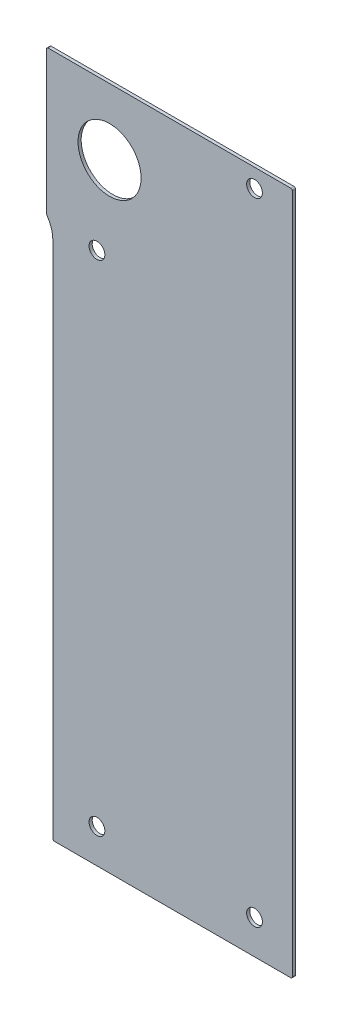
SolidWorks part; units mm, degrees
ref_plane "Ebene vorne" through (0, 0, 0) normal (0, 0, 1) x (1, 0, 0)
ref_plane "Ebene oben" through (0, 0, 0) normal (0, 1, 0) x (1, 0, 0)
ref_plane "Ebene rechts" through (0, 0, 0) normal (1, 0, 0) x (0, 0, -1)
sketch "Sketch1" plane through (0, 0, 0) normal (0, 0, 1) x (1, 0, 0)
  line L0 (2, 0) -> (2, 175) construction
  line L1 (0, 0) -> (76, 0)
  line L2 (0, 0) -> (0, 175)
  line L3 (-19.55, 217) -> (-32, 217)
  line L4 (76, 0) -> (76, 217)
  line L5 (0, 175) -> (-32, 175)
  line L6 (-19.55, 217) -> (-19.55, 212)
  line L7 (76, 217) -> (-12.55, 217)
  line L8 (-32, 175) -> (-32, 217)
  line L9 (-19.55, 212) -> (-12.55, 212)
  line L10 (-12.55, 217) -> (-12.55, 212)
  line L11 (-19.55, 205.875) -> (-12.55, 205.875) construction
  line L12 (-19.55, 207) -> (-12.55, 207)
  line L13 (-19.55, 204.75) -> (-12.55, 204.75)
  circle A0 centre (14, 169.15) radius 2.5
  circle A1 centre (14, 10.85) radius 2.5
  circle A2 centre (64, 10.85) radius 2.5
  circle A3 centre (64, 211.15) radius 2.5
  circle A4 centre (18, 196) radius 10
  arc A5 (-19.55, 207) -> (-19.55, 204.75) centre (-19.55, 205.875) ccw
  arc A6 (-12.55, 204.75) -> (-12.55, 207) centre (-12.55, 205.875) ccw
  point P25 (-16.05, 205.875)
  dimension "D7" = 5
  dimension "D17" = 20
  dimension "D11" = 1.125
  dimension "D1" = 76
  dimension "D2" = 217
  dimension "D3" = 108
  dimension "D4" = 42
  dimension "D5" = 2
  dimension "D6" = 12
  dimension "D8" = 10.85
  dimension "D9" = 7
  dimension "D10" = 5
  dimension "D12" = 12.45
  dimension "D13" = 12
  dimension "D14" = 5.85
  dimension "D15" = 58
  dimension "D16" = 21
  dimension "D18" = 5.85
  dimension "D19" = 5
extrude "Boss-Extrude1" add sketch "Sketch1" along normal blind 1
sketch "Sketch2" plane through (0, 0, 1) normal (0, 0, 1) x (1, 0, 0)
  line L0 (-16.05, 212) -> (-16.05, 213.3573) construction
  line L2 (-12.55, 212) -> (-19.55, 212) construction
  line L4 (-13.6107, 213.0607) -> (-13.6107, 212) construction
  line L5 (-13.6107, 213.0607) -> (-12.55, 213.0607) construction
  line L6 (-12.55, 217) -> (-12.55, 212) construction
  circle A1 centre (-13.6107, 213.0607) radius 1.5
  circle A3 centre (-18.4893, 213.0607) radius 1.5
  dimension "D1" = 3
extrude "Cut-Extrude1" cut sketch "Sketch2" against normal through all
fillet "Fillet1" radius 0.5 6 edges at (76, 217, 0.5) (76, 0, 0.5) (0, 0, 0.5) (-19.55, 217, 0.5) (-12.55, 217, 0.5) (-32, 217, 0.5)
fillet "Fillet2" radius 10 2 edges at (0, 175, 0.5) (-32, 175, 0.5)
ref_plane "Plane1" through (76, 216.5, 1) normal (0, 1, 0) x (1, 0, 0)
sketch "Sketch4" plane through (0, 0, 1) normal (0, 0, 1) x (1, 0, 0)
  line L0 (-2, 227.3367) -> (-2, 146.8403) construction
  line L1 (76, 0.5) -> (76, 216.5) construction
  line L2 (-2, 217) -> (-2, 171)
  line L3 (75.5, 217) -> (-12.05, 217) construction
  line L4 (-20.05, 217) -> (-31.5, 217) construction
  line L5 (-32, 216.5) -> (-32, 185) construction
  line L6 (-19.55, 214.1213) -> (-19.55, 216.5) construction
  line L7 (-14.6713, 212) -> (-17.4287, 212) construction
  line L8 (-12.55, 216.5) -> (-12.55, 214.1213) construction
  line L9 (-22, 175) -> (-10, 175) construction
  line L10 (-20.05, 217) -> (-31.5, 217)
  line L11 (-32, 216.5) -> (-32, 185)
  line L12 (-19.55, 214.1213) -> (-19.55, 216.5)
  line L13 (-14.6713, 212) -> (-17.4287, 212)
  line L14 (-12.55, 216.5) -> (-12.55, 214.1213)
  line L15 (-22, 175) -> (-10, 175)
  line L16 (-12.05, 217) -> (-2, 217)
  arc A0 (0, 165) -> (-10, 175) centre (-10, 165) ccw construction
  arc A1 (-31.5, 217) -> (-32, 216.5) centre (-31.5, 216.5) ccw construction
  arc A2 (-19.55, 214.1213) -> (-17.4287, 212) centre (-18.4893, 213.0607) ccw construction
  arc A3 (-19.55, 216.5) -> (-20.05, 217) centre (-20.05, 216.5) ccw construction
  arc A4 (-14.6713, 212) -> (-12.55, 214.1213) centre (-13.6107, 213.0607) ccw construction
  arc A5 (-12.05, 217) -> (-12.55, 216.5) centre (-12.05, 216.5) ccw construction
  arc A6 (-32, 185) -> (-22, 175) centre (-22, 185) ccw construction
  arc A7 (-31.5, 217) -> (-32, 216.5) centre (-31.5, 216.5) ccw
  arc A8 (-19.55, 214.1213) -> (-17.4287, 212) centre (-18.4893, 213.0607) ccw
  arc A9 (-19.55, 216.5) -> (-20.05, 217) centre (-20.05, 216.5) ccw
  arc A10 (-14.6713, 212) -> (-12.55, 214.1213) centre (-13.6107, 213.0607) ccw
  arc A11 (-12.05, 217) -> (-12.55, 216.5) centre (-12.05, 216.5) ccw
  arc A12 (-32, 185) -> (-22, 175) centre (-22, 185) ccw
  arc A13 (-10, 175) -> (-2, 171) centre (-20.8077, 143.3845) cw
  dimension "D1" = 78
extrude "Cut-Extrude2" cut sketch "Sketch4" against normal blind 10
fillet "Fillet3" radius 2 1 edges at (-2, 171, 0.5)
fillet "Fillet4" radius 0.5 1 edges at (-2, 217, 0.5)
ref_plane "Plane2" through (-2, 216.5, 1) normal (0, 1, 0) x (1, 0, 0)
